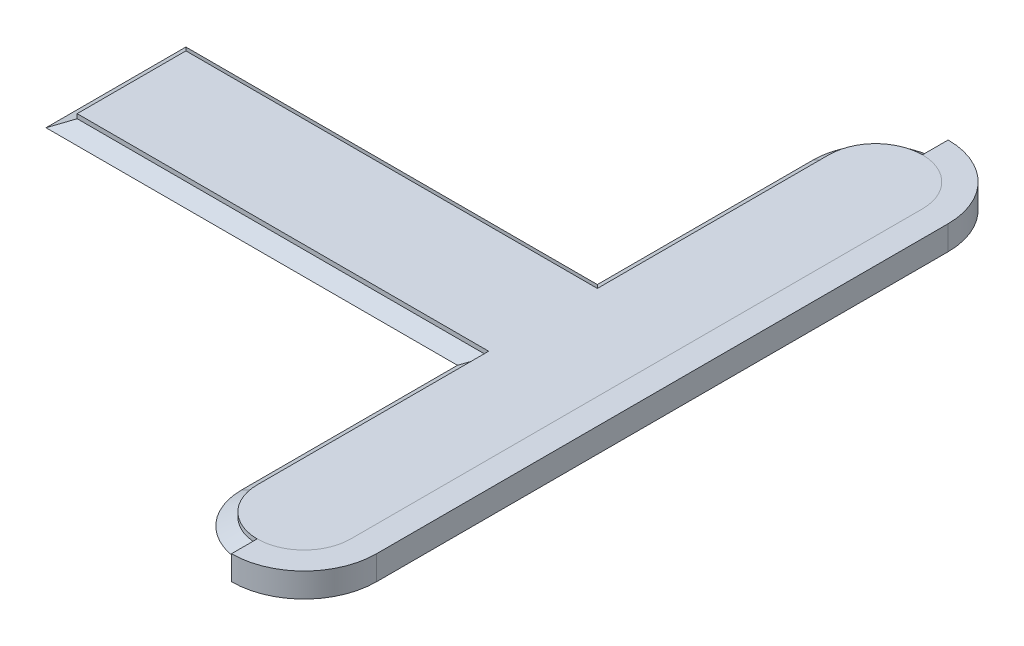
SolidWorks part; units mm, degrees
ref_plane "Front Plane" through (0, 0, 0) normal (0, 0, 1) x (1, 0, 0)
ref_plane "Top Plane" through (0, 0, 0) normal (0, 1, 0) x (1, 0, 0)
ref_plane "Right Plane" through (0, 0, 0) normal (1, 0, 0) x (0, 0, -1)
sketch "Sketch1" plane through (0, 0, 0) normal (0, 1, 0) x (1, 0, 0)
  line L0 (0, -13.4216) -> (101.6, -13.4216)
  line L1 (101.6, -13.4216) -> (101.6, -70.5716)
  line L2 (124.714, -70.5716) -> (124.714, 70.5716)
  line L3 (101.6, 70.5716) -> (101.6, 13.4216)
  line L4 (101.6, 13.4216) -> (0, 13.4216)
  line L5 (0, 13.4216) -> (0, -13.4216)
  arc A0 (101.6, -70.5716) -> (124.714, -70.5716) centre (113.157, -70.5716) ccw
  arc A1 (124.714, 70.5716) -> (101.6, 70.5716) centre (113.157, 70.5716) ccw
  point P12 (0, 0)
extrude "Boss-Extrude1" add sketch "Sketch1" along normal blind 6
sketch "Sketch2" plane through (0, 0, 0) normal (0, 0, 1) x (1, 0, 0)
  line L0 (0, 3) -> (101.6, 3)
  line L1 (0, 6) -> (0, 0) construction
  line L2 (101.6, 6) -> (101.6, 0) construction
split line "Split Line1"
sketch "Sketch3" plane through (0, 0, 0) normal (1, 0, 0) x (0, 0, -1)
  line L0 (82.1286, 3) -> (-82.1286, 3)
  line L1 (82.1286, 0) -> (82.1286, 6) construction
  line L2 (-82.1286, 6) -> (-82.1286, 0) construction
split line "Split Line2"
curve "CompCurve1"
ref_plane "Plane1" through (113.157, 0, 0) normal (1, 0, 0) x (0, 0, -1)
sketch "Sketch4" plane through (113.157, 0, 0) normal (1, 0, 0) x (0, 0, -1)
  line L0 (82.1286, 4.9103) -> (82.1286, 1.0603)
  line L6 (82.1286, 3) -> (82.1286, 6) construction
  line L7 (82.1286, 0) -> (82.1286, 3) construction
  line L8 (82.1286, 4.9103) -> (85.9786, 2.9853)
  line L9 (82.1286, 1.0603) -> (85.9786, 2.9853)
  dimension "D1" = 3.85
  dimension "D2" = 3.85
sweep "Sweep1" add profiles "Sketch4" path "CompCurve1"
sketch "Sketch5" plane through (0, 6, 0) normal (0, 1, 0) x (1, 0, 0)
  line L0 (131.064, -70.5716) -> (131.064, 70.5716)
  line L1 (113.157, 88.4786) -> (113.157, 82.1286)
  line L2 (124.714, 70.5716) -> (124.714, -70.5716)
  line L3 (113.157, -82.1286) -> (113.157, -88.4786)
  line L4 (113.157, -82.1286) -> (113.157, -79.7009) construction
  line L5 (113.157, 82.1286) -> (113.157, 81.4216) construction
  line L6 (113.157, -3.3) -> (113.157, 3.3) construction
  arc A0 (131.064, 70.5716) -> (113.157, 88.4786) centre (113.157, 70.5716) ccw
  arc A1 (124.714, 70.5716) -> (113.157, 82.1286) centre (113.157, 70.5716) ccw
  arc A2 (113.157, -82.1286) -> (124.714, -70.5716) centre (113.157, -70.5716) ccw
  arc A3 (113.157, -88.4786) -> (131.064, -70.5716) centre (113.157, -70.5716) ccw
  arc A4 (124.714, 70.5716) -> (101.6, 70.5716) centre (113.157, 70.5716) ccw construction
  arc A5 (101.6, -70.5716) -> (124.714, -70.5716) centre (113.157, -70.5716) ccw construction
  dimension "D1" = 6.35
extrude "Boss-Extrude2" add sketch "Sketch5" along a picked direction on the side against the normal up to surface (6 mm away) separate body
